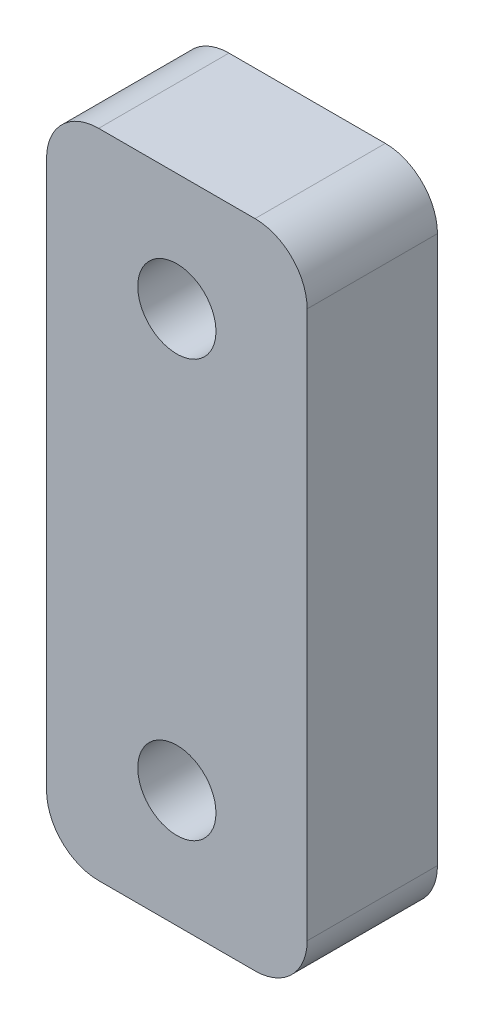
SolidWorks part; units mm, degrees
ref_plane "前视基准面" through (0, 0, 0) normal (0, 0, 1) x (1, 0, 0)
ref_plane "上视基准面" through (0, 0, 0) normal (0, 1, 0) x (1, 0, 0)
ref_plane "右视基准面" through (0, 0, 0) normal (1, 0, 0) x (0, 0, -1)
sketch "草图2" plane through (0, 0, 0) normal (0, 0, 1) x (1, 0, 0)
  line L1 (5, -12.5) -> (-5, -12.5)
  line L2 (5, -12.5) -> (5, 12.5)
  line L3 (5, 12.5) -> (-5, 12.5)
  line L4 (-5, -12.5) -> (-5, 12.5)
  line L5 (5, -12.5) -> (-5, 12.5) construction
  line L6 (5, 12.5) -> (-5, -12.5) construction
  point P0 (0, 0)
  dimension "D1" = 10
  dimension "D2" = 25
extrude "凸台-拉伸1" add sketch "草图2" along normal blind 5
sketch "草图3" plane through (0, 0, 5) normal (0, 0, 1) x (1, 0, 0)
  line L0 (0, -8) -> (0, 8) construction
  line L2 (0, 0) -> (5, 0) construction
  line L3 (5, -12.5) -> (5, 12.5) construction
  circle A0 centre (0, -8) radius 1.5
  circle A1 centre (0, 8) radius 1.5
  dimension "D1" = 3
  dimension "D2" = 16
extrude "切除-拉伸1" cut sketch "草图3" against normal through all
fillet "圆角1" radius 2 4 edges at (5, -12.5, 2.5) (-5, -12.5, 2.5) (5, 12.5, 2.5) (-5, 12.5, 2.5)
